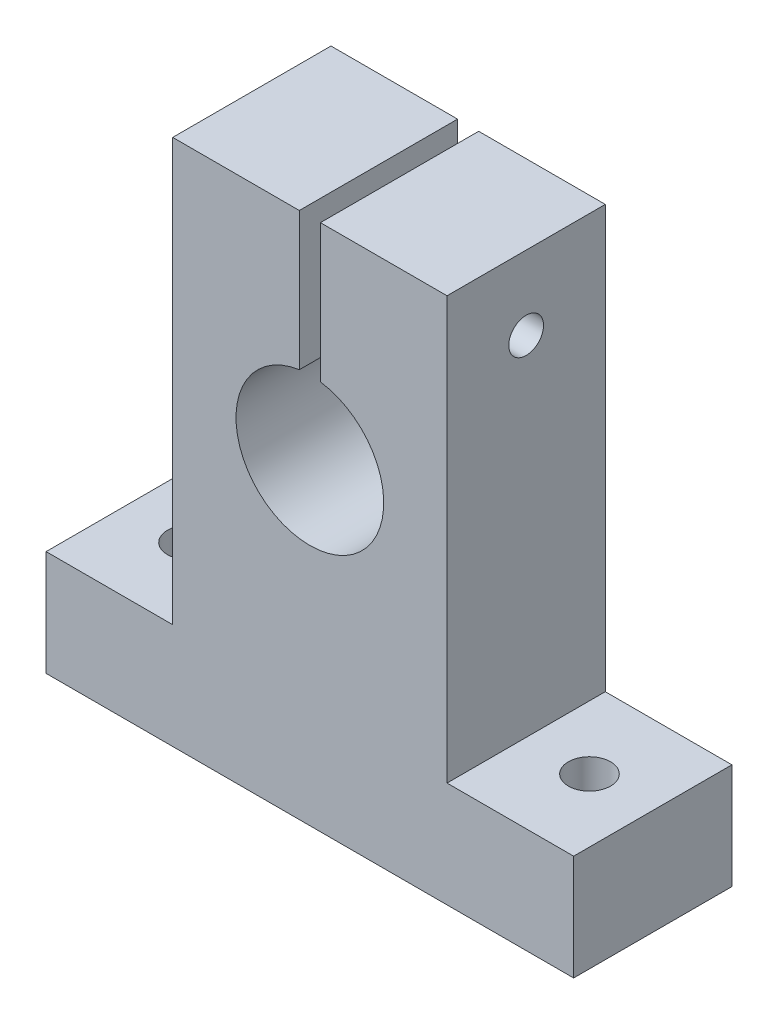
SolidWorks part; units mm, degrees
ref_plane "Front Plane" through (0, 0, 0) normal (0, 0, 1) x (1, 0, 0)
ref_plane "Top Plane" through (0, 0, 0) normal (0, 1, 0) x (1, 0, 0)
ref_plane "Right Plane" through (0, 0, 0) normal (1, 0, 0) x (0, 0, -1)
sketch "Sketch1" plane through (0, 0, 0) normal (0, 0, 1) x (1, 0, 0)
  line L1 (-26, 0) -> (-26, -40)
  line L2 (-26, -40) -> (-38, -40)
  line L3 (-38, -40) -> (-38, -50)
  line L4 (-38, -50) -> (12, -50)
  line L5 (12, -50) -> (12, -40)
  line L6 (12, -40) -> (0, -40)
  line L7 (0, -40) -> (0, 0)
  line L8 (-14, 0) -> (-14, -13.0718)
  line L9 (-12, 0) -> (-12, -13.0718)
  line L10 (-26, 0) -> (-14, 0)
  line L11 (-12, 0) -> (0, 0)
  arc A7 (-14, -13.0718) -> (-12, -13.0718) centre (-13, -20) ccw
  point P11 (0, -40)
  point P14 (-26, -40)
  point P17 (12, -40)
  point P20 (-38, -40)
  point P23 (0, 0)
  dimension "D6" = 13
  dimension "D7" = 7
  dimension "D9" = 1
  dimension "D14" = 0
  dimension "D1" = 50
  dimension "D2" = 12
  dimension "D3" = 12
  dimension "D4" = 10
  dimension "D5" = 50
  dimension "D8" = 2
  dimension "D11" = 30
  dimension "D13" = 50
extrude "Boss-Extrude1" add sketch "Sketch1" along normal blind 15
sketch "Sketch5" plane through (0, -40, 0) normal (0, 1, 0) x (1, 0, 0)
  line L0 (12, 0) -> (0, 0) construction
  line L1 (-26, 0) -> (-38, 0) construction
  line L4 (12, -15) -> (12, 0) construction
  line L5 (-38, -15) -> (-38, 0) construction
  circle A0 centre (6, -7.5) radius 2
  circle A1 centre (-32, -7.5) radius 2
  dimension "D3" = 4
  dimension "D4" = 4
  dimension "D1" = 7.5
  dimension "D2" = 7.5
  dimension "D5" = 6
  dimension "D6" = 6
extrude "Cut-Extrude3" cut sketch "Sketch5" against normal blind 15
hole_wizard "Chambrage pour vis à tête hexagonale M41" positions "Esquisse1" profile "Esquisse2" counterbore size "M4" standard "ISO"
sketch "Esquisse1" plane through (-26, 0, 0) normal (-1, 0, 0) x (0, 0, 1)
  line L0 (15, 0) -> (0, 0) construction
  point P0 (7.5699, -7)
  dimension "D1" = 7
sketch "Esquisse2" plane through (-26, -7, 7.5699) normal (0, 1, 0) x (0, 0, 1)
  line L0 (0, 0) -> (0, 12)
  line L1 (0, 12) -> (2.15, 12)
  line L3 (2.15, 12) -> (2.15, 4.4)
  line L4 (2.15, 4.4) -> (4, 4.4)
  line L5 (4, 4.4) -> (4, 0)
  line L7 (4, 0) -> (0, 0)
  line L11 (0, -6.35) -> (0, 107.95) construction
  dimension "Diamètre du perçage jusqu'au prochain" = 4.3
  dimension "Profondeur du perçage jusqu'au prochain" = 12
  dimension "Diamètre du chambrage" = 8
  dimension "Profondeur du chambrage" = 4.4
hole_wizard "Trou taraudé M41" positions "Esquisse3" profile "Esquisse4" tap size "M4" standard "ISO" end condition up to next
sketch "Esquisse3" plane through (0, 0, 0) normal (1, 0, 0) x (0, 0, -1)
  line L0 (-15, -40) -> (-15, 0) construction
  line L1 (-15, 0) -> (0, 0) construction
  point P0 (-7.5, -7)
  point P9 (-6.6587, -10.3627)
  dimension "D1" = 7.5
  dimension "D2" = 7
sketch "Esquisse4" plane through (0, -7, 7.5) normal (0, 1, 0) x (0, 0, -1)
  line L0 (0, 0) -> (0, 12)
  line L1 (0, 12) -> (1.65, 12)
  line L2 (1.65, 12) -> (1.65, 0)
  line L5 (1.65, 0) -> (0, 0)
  line L11 (0, -6.35) -> (0, 107.95) construction
  dimension "Diamètre du trou pour taraudage jusqu'au prochain" = 3.3
  dimension "Profondeur du trou pour taraudage jusqu'au prochain" = 12
cosmetic thread "Filetage de perçage1" parameters "D2"=4
